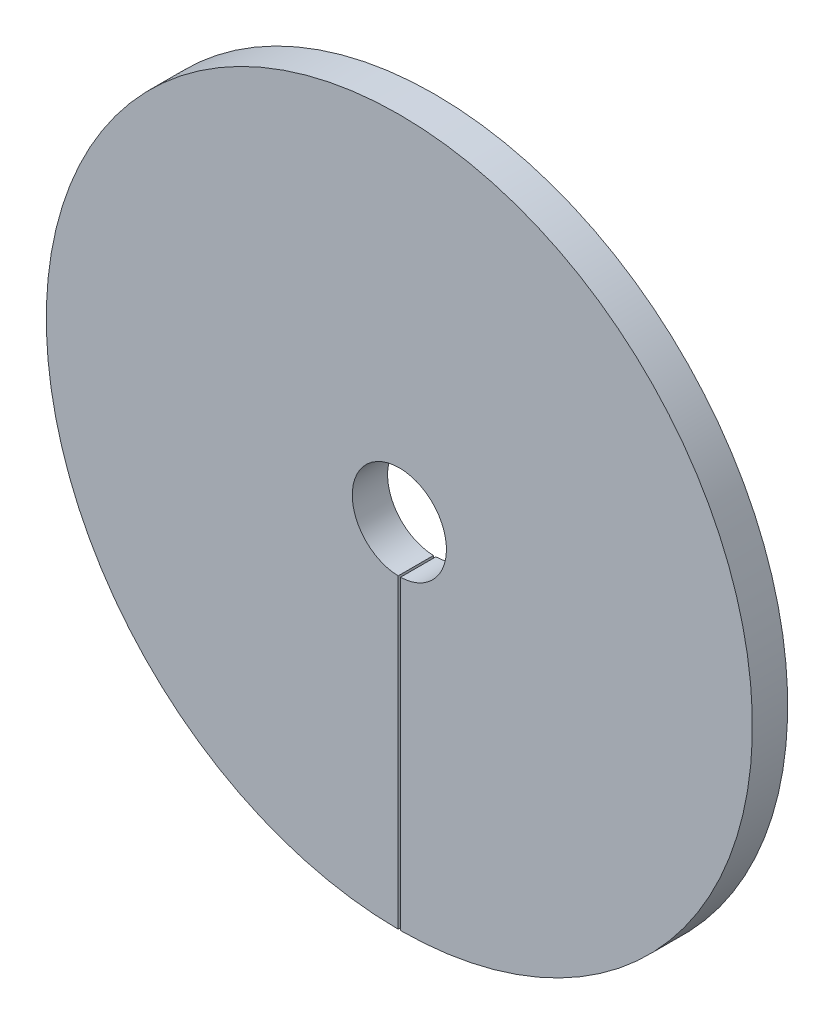
SolidWorks part; units mm, degrees
ref_plane "Plano frontal" through (0, 0, 0) normal (0, 0, 1) x (1, 0, 0)
ref_plane "Plano superior" through (0, 0, 0) normal (0, 1, 0) x (1, 0, 0)
ref_plane "Plano direito" through (0, 0, 0) normal (1, 0, 0) x (0, 0, -1)
sketch "Esboço1" plane through (0, 0, 0) normal (0, 0, 1) x (1, 0, 0)
  line L0 (0.1, -3.9987) -> (0.1, -29.9998)
  line L1 (-0.1, -3.9987) -> (-0.1, -29.9998)
  line L2 (0, 0) -> (0, 8.5463) construction
  arc A0 (0.1, -29.9998) -> (-0.1, -29.9998) centre (0, 0) ccw
  arc A1 (0.1, -3.9987) -> (-0.1, -3.9987) centre (0, 0) ccw
  dimension "D1" = 60
  dimension "D2" = 8
  dimension "D3" = 0.2
extrude "Ressalto-extrusão1" add sketch "Esboço1" along normal blind 3
